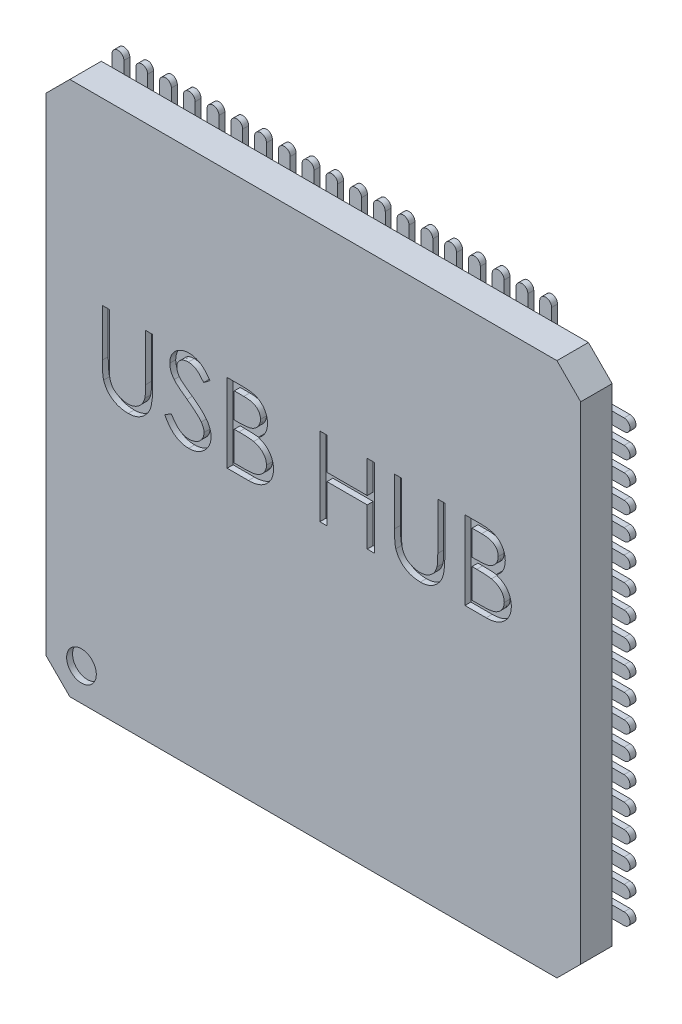
SolidWorks part; units mm, degrees
ref_plane "Front" through (0, 0, 0) normal (0, 0, 1) x (1, 0, 0)
ref_plane "Top" through (0, 0, 0) normal (0, 1, 0) x (1, 0, 0)
ref_plane "Right" through (0, 0, 0) normal (1, 0, 0) x (0, 0, -1)
ref_plane "Plan1" through (0, 0, 6.6297) normal (0, 0, -1) x (-1, 0, 0)
sketch "Esquisse1" plane through (0, 0, 6.6297) normal (0, 0, -1) x (-1, 0, 0)
  line L0 (-11.8985, 7.5604) -> (-11.8985, -1.4396)
  line L1 (-11.8985, -1.4396) -> (-2.8985, -1.4396)
  line L2 (-2.8985, -1.4396) -> (-2.8985, 7.5604)
  line L3 (-2.8985, 7.5604) -> (-11.8985, 7.5604)
extrude "Boss.-Extru.1" add sketch "Esquisse1" against normal blind 0.53
hole_wizard "Diamètre du perçage Ø0.5 (0.5)1" positions "Esquisse3" profile "Esquisse2" hole size "Ø0.5" standard "Ansi Metric"
sketch "Esquisse3" plane through (0, 0, 7.1597) normal (0, 0, 1) x (1, 0, 0)
  point P0 (3.4947, -0.8917)
sketch "Esquisse2" plane through (3.4947, -0.8917, 7.1597) normal (1, 0, 0) x (0, -1, 0)
  line L0 (0, 0) -> (0, 0.1)
  line L1 (0, 0.1) -> (0.25, 0.1)
  line L2 (0.25, 0.1) -> (0.25, 0)
  line L5 (0.25, 0) -> (0, 0)
  line L10 (0, 0.1) -> (-0.25, 0.1) construction
  line L11 (0, -6.35) -> (0, 107.95) construction
  dimension "Diamètre du perçage" = 0.5
  dimension "Profondeur du perçage" = 0.1
  dimension "Angle de pointe" = 180
chamfer "Chanfrein1" distance 0.4 angle 45 4 edges at (2.8985, 7.5604, 6.8947) (11.8985, 7.5604, 6.8947) (11.8985, -1.4396, 6.8947) (2.8985, -1.4396, 6.8947)
sketch "Esquisse4" plane through (0, 0, 6.6297) normal (0, 0, -1) x (-1, 0, 0)
  line L0 (-7.3985, 7.5604) -> (-7.3985, -1.4396) construction
  line L1 (-3.2985, 7.5604) -> (-11.4985, 7.5604) construction
  line L2 (-11.4985, -1.4396) -> (-3.2985, -1.4396) construction
  line L3 (-2.8985, 3.0604) -> (-11.8985, 3.0604) construction
  line L4 (-2.8985, -1.0396) -> (-2.8985, 7.1604) construction
  line L5 (-11.8985, 7.1604) -> (-11.8985, -1.0396) construction
  line L6 (-3.0985, 3.0604) -> (-2.6985, 3.0604) construction
  line L7 (-3.0985, 3.1604) -> (-2.6985, 3.1604)
  line L8 (-3.0985, 2.9604) -> (-2.6985, 2.9604)
  line L9 (-3.0985, 3.4604) -> (-2.6985, 3.4604) construction
  line L10 (-3.0985, 3.5604) -> (-2.6985, 3.5604)
  line L11 (-3.0985, 3.3604) -> (-2.6985, 3.3604)
  line L12 (-3.0985, 3.8604) -> (-2.6985, 3.8604) construction
  line L13 (-3.0985, 3.9604) -> (-2.6985, 3.9604)
  line L14 (-3.0985, 3.7604) -> (-2.6985, 3.7604)
  line L15 (-3.0985, 4.2604) -> (-2.6985, 4.2604) construction
  line L16 (-3.0985, 4.3604) -> (-2.6985, 4.3604)
  line L17 (-3.0985, 4.1604) -> (-2.6985, 4.1604)
  line L18 (-3.0985, 3.8604) -> (-2.6985, 3.8604) construction
  line L19 (-3.0985, 3.9604) -> (-2.6985, 3.9604)
  line L20 (-3.0985, 3.7604) -> (-2.6985, 3.7604)
  line L21 (-3.0985, 4.2604) -> (-2.6985, 4.2604) construction
  line L22 (-3.0985, 4.3604) -> (-2.6985, 4.3604)
  line L23 (-3.0985, 4.1604) -> (-2.6985, 4.1604)
  line L24 (-3.0985, 4.6604) -> (-2.6985, 4.6604) construction
  line L25 (-3.0985, 4.7604) -> (-2.6985, 4.7604)
  line L26 (-3.0985, 4.5604) -> (-2.6985, 4.5604)
  line L27 (-3.0985, 4.2604) -> (-2.6985, 4.2604) construction
  line L28 (-3.0985, 4.3604) -> (-2.6985, 4.3604)
  line L29 (-3.0985, 4.1604) -> (-2.6985, 4.1604)
  line L30 (-3.0985, 4.6604) -> (-2.6985, 4.6604) construction
  line L31 (-3.0985, 4.7604) -> (-2.6985, 4.7604)
  line L32 (-3.0985, 4.5604) -> (-2.6985, 4.5604)
  line L33 (-3.0985, 5.0604) -> (-2.6985, 5.0604) construction
  line L34 (-3.0985, 5.1604) -> (-2.6985, 5.1604)
  line L35 (-3.0985, 4.9604) -> (-2.6985, 4.9604)
  line L36 (-3.0985, 4.6604) -> (-2.6985, 4.6604) construction
  line L37 (-3.0985, 4.7604) -> (-2.6985, 4.7604)
  line L38 (-3.0985, 4.5604) -> (-2.6985, 4.5604)
  line L39 (-3.0985, 5.0604) -> (-2.6985, 5.0604) construction
  line L40 (-3.0985, 5.1604) -> (-2.6985, 5.1604)
  line L41 (-3.0985, 4.9604) -> (-2.6985, 4.9604)
  line L42 (-3.0985, 5.4604) -> (-2.6985, 5.4604) construction
  line L43 (-3.0985, 5.5604) -> (-2.6985, 5.5604)
  line L44 (-3.0985, 5.3604) -> (-2.6985, 5.3604)
  line L45 (-3.0985, 5.0604) -> (-2.6985, 5.0604) construction
  line L46 (-3.0985, 5.1604) -> (-2.6985, 5.1604)
  line L47 (-3.0985, 4.9604) -> (-2.6985, 4.9604)
  line L48 (-3.0985, 5.4604) -> (-2.6985, 5.4604) construction
  line L49 (-3.0985, 5.5604) -> (-2.6985, 5.5604)
  line L50 (-3.0985, 5.3604) -> (-2.6985, 5.3604)
  line L51 (-3.0985, 5.8604) -> (-2.6985, 5.8604) construction
  line L52 (-3.0985, 5.9604) -> (-2.6985, 5.9604)
  line L53 (-3.0985, 5.7604) -> (-2.6985, 5.7604)
  line L54 (-3.0985, 5.4604) -> (-2.6985, 5.4604) construction
  line L55 (-3.0985, 5.5604) -> (-2.6985, 5.5604)
  line L56 (-3.0985, 5.3604) -> (-2.6985, 5.3604)
  line L57 (-3.0985, 5.8604) -> (-2.6985, 5.8604) construction
  line L58 (-3.0985, 5.9604) -> (-2.6985, 5.9604)
  line L59 (-3.0985, 5.7604) -> (-2.6985, 5.7604)
  line L60 (-3.0985, 6.2604) -> (-2.6985, 6.2604) construction
  line L61 (-3.0985, 6.3604) -> (-2.6985, 6.3604)
  line L62 (-3.0985, 6.1604) -> (-2.6985, 6.1604)
  line L63 (-3.0985, 5.8604) -> (-2.6985, 5.8604) construction
  line L64 (-3.0985, 5.9604) -> (-2.6985, 5.9604)
  line L65 (-3.0985, 5.7604) -> (-2.6985, 5.7604)
  line L66 (-3.0985, 6.2604) -> (-2.6985, 6.2604) construction
  line L67 (-3.0985, 6.3604) -> (-2.6985, 6.3604)
  line L68 (-3.0985, 6.1604) -> (-2.6985, 6.1604)
  line L69 (-3.0985, 6.6604) -> (-2.6985, 6.6604) construction
  line L70 (-3.0985, 6.7604) -> (-2.6985, 6.7604)
  line L71 (-3.0985, 6.5604) -> (-2.6985, 6.5604)
  line L72 (-3.0985, 3.4604) -> (-2.6985, 3.4604) construction
  line L73 (-3.0985, 3.5604) -> (-2.6985, 3.5604)
  line L74 (-3.0985, 3.3604) -> (-2.6985, 3.3604)
  line L75 (-3.0985, 3.8604) -> (-2.6985, 3.8604) construction
  line L76 (-3.0985, 3.9604) -> (-2.6985, 3.9604)
  line L77 (-3.0985, 3.7604) -> (-2.6985, 3.7604)
  line L78 (-3.0985, 4.2604) -> (-2.6985, 4.2604) construction
  line L79 (-3.0985, 4.3604) -> (-2.6985, 4.3604)
  line L80 (-3.0985, 4.1604) -> (-2.6985, 4.1604)
  line L81 (-3.0985, 4.6604) -> (-2.6985, 4.6604) construction
  line L82 (-3.0985, 4.7604) -> (-2.6985, 4.7604)
  line L83 (-3.0985, 4.5604) -> (-2.6985, 4.5604)
  line L84 (-3.0985, 5.0604) -> (-2.6985, 5.0604) construction
  line L85 (-3.0985, 5.1604) -> (-2.6985, 5.1604)
  line L86 (-3.0985, 4.9604) -> (-2.6985, 4.9604)
  line L87 (-3.0985, 5.4604) -> (-2.6985, 5.4604) construction
  line L88 (-3.0985, 5.5604) -> (-2.6985, 5.5604)
  line L89 (-3.0985, 5.3604) -> (-2.6985, 5.3604)
  line L90 (-3.0985, 2.6604) -> (-2.6985, 2.6604) construction
  line L91 (-3.0985, 2.7604) -> (-2.6985, 2.7604)
  line L92 (-3.0985, 2.5604) -> (-2.6985, 2.5604)
  line L93 (-3.0985, 2.2604) -> (-2.6985, 2.2604) construction
  line L94 (-3.0985, 2.3604) -> (-2.6985, 2.3604)
  line L95 (-3.0985, 2.1604) -> (-2.6985, 2.1604)
  line L96 (-3.0985, 1.8604) -> (-2.6985, 1.8604) construction
  line L97 (-3.0985, 1.9604) -> (-2.6985, 1.9604)
  line L98 (-3.0985, 1.7604) -> (-2.6985, 1.7604)
  line L99 (-3.0985, 1.4604) -> (-2.6985, 1.4604) construction
  line L100 (-3.0985, 1.5604) -> (-2.6985, 1.5604)
  line L101 (-3.0985, 1.3604) -> (-2.6985, 1.3604)
  line L102 (-3.0985, 1.0604) -> (-2.6985, 1.0604) construction
  line L103 (-3.0985, 1.1604) -> (-2.6985, 1.1604)
  line L104 (-3.0985, 0.9604) -> (-2.6985, 0.9604)
  line L105 (-3.0985, 0.6604) -> (-2.6985, 0.6604) construction
  line L106 (-3.0985, 0.7604) -> (-2.6985, 0.7604)
  line L107 (-3.0985, 0.5604) -> (-2.6985, 0.5604)
  line L108 (-3.0985, 0.2604) -> (-2.6985, 0.2604) construction
  line L109 (-3.0985, 0.3604) -> (-2.6985, 0.3604)
  line L110 (-3.0985, 0.1604) -> (-2.6985, 0.1604)
  line L111 (-3.0985, -0.1396) -> (-2.6985, -0.1396) construction
  line L112 (-3.0985, -0.0396) -> (-2.6985, -0.0396)
  line L113 (-3.0985, -0.2396) -> (-2.6985, -0.2396)
  line L114 (-3.0985, -0.5396) -> (-2.6985, -0.5396) construction
  line L115 (-3.0985, -0.4396) -> (-2.6985, -0.4396)
  line L116 (-3.0985, -0.6396) -> (-2.6985, -0.6396)
  line L117 (-11.6985, -0.5396) -> (-12.0985, -0.5396) construction
  line L118 (-11.6985, -0.4396) -> (-12.0985, -0.4396)
  line L119 (-11.6985, -0.6396) -> (-12.0985, -0.6396)
  line L120 (-11.6985, -0.1396) -> (-12.0985, -0.1396) construction
  line L121 (-11.6985, -0.0396) -> (-12.0985, -0.0396)
  line L122 (-11.6985, -0.2396) -> (-12.0985, -0.2396)
  line L123 (-11.6985, 0.2604) -> (-12.0985, 0.2604) construction
  line L124 (-11.6985, 0.3604) -> (-12.0985, 0.3604)
  line L125 (-11.6985, 0.1604) -> (-12.0985, 0.1604)
  line L126 (-11.6985, 0.6604) -> (-12.0985, 0.6604) construction
  line L127 (-11.6985, 0.7604) -> (-12.0985, 0.7604)
  line L128 (-11.6985, 0.5604) -> (-12.0985, 0.5604)
  line L129 (-11.6985, 1.0604) -> (-12.0985, 1.0604) construction
  line L130 (-11.6985, 1.1604) -> (-12.0985, 1.1604)
  line L131 (-11.6985, 0.9604) -> (-12.0985, 0.9604)
  line L132 (-11.6985, 1.4604) -> (-12.0985, 1.4604) construction
  line L133 (-11.6985, 1.5604) -> (-12.0985, 1.5604)
  line L134 (-11.6985, 1.3604) -> (-12.0985, 1.3604)
  line L135 (-11.6985, 1.8604) -> (-12.0985, 1.8604) construction
  line L136 (-11.6985, 1.9604) -> (-12.0985, 1.9604)
  line L137 (-11.6985, 1.7604) -> (-12.0985, 1.7604)
  line L138 (-11.6985, 2.2604) -> (-12.0985, 2.2604) construction
  line L139 (-11.6985, 2.3604) -> (-12.0985, 2.3604)
  line L140 (-11.6985, 2.1604) -> (-12.0985, 2.1604)
  line L141 (-11.6985, 2.6604) -> (-12.0985, 2.6604) construction
  line L142 (-11.6985, 2.7604) -> (-12.0985, 2.7604)
  line L143 (-11.6985, 2.5604) -> (-12.0985, 2.5604)
  line L144 (-11.6985, 3.0604) -> (-12.0985, 3.0604) construction
  line L145 (-11.6985, 3.1604) -> (-12.0985, 3.1604)
  line L146 (-11.6985, 2.9604) -> (-12.0985, 2.9604)
  line L147 (-11.6985, 3.4604) -> (-12.0985, 3.4604) construction
  line L148 (-11.6985, 3.5604) -> (-12.0985, 3.5604)
  line L149 (-11.6985, 3.3604) -> (-12.0985, 3.3604)
  line L150 (-11.6985, 3.8604) -> (-12.0985, 3.8604) construction
  line L151 (-11.6985, 3.9604) -> (-12.0985, 3.9604)
  line L152 (-11.6985, 3.7604) -> (-12.0985, 3.7604)
  line L153 (-11.6985, 4.2604) -> (-12.0985, 4.2604) construction
  line L154 (-11.6985, 4.3604) -> (-12.0985, 4.3604)
  line L155 (-11.6985, 4.1604) -> (-12.0985, 4.1604)
  line L156 (-11.6985, 4.6604) -> (-12.0985, 4.6604) construction
  line L157 (-11.6985, 4.7604) -> (-12.0985, 4.7604)
  line L158 (-11.6985, 4.5604) -> (-12.0985, 4.5604)
  line L159 (-11.6985, 5.0604) -> (-12.0985, 5.0604) construction
  line L160 (-11.6985, 5.1604) -> (-12.0985, 5.1604)
  line L161 (-11.6985, 4.9604) -> (-12.0985, 4.9604)
  line L162 (-11.6985, 5.4604) -> (-12.0985, 5.4604) construction
  line L163 (-11.6985, 5.5604) -> (-12.0985, 5.5604)
  line L164 (-11.6985, 5.3604) -> (-12.0985, 5.3604)
  line L165 (-11.6985, 5.8604) -> (-12.0985, 5.8604) construction
  line L166 (-11.6985, 5.9604) -> (-12.0985, 5.9604)
  line L167 (-11.6985, 5.7604) -> (-12.0985, 5.7604)
  line L168 (-11.6985, 6.2604) -> (-12.0985, 6.2604) construction
  line L169 (-11.6985, 6.3604) -> (-12.0985, 6.3604)
  line L170 (-11.6985, 6.1604) -> (-12.0985, 6.1604)
  line L171 (-11.6985, 6.6604) -> (-12.0985, 6.6604) construction
  line L172 (-11.6985, 6.7604) -> (-12.0985, 6.7604)
  line L173 (-11.6985, 6.5604) -> (-12.0985, 6.5604)
  line L174 (-2.8985, 3.0604) -> (-11.8985, 3.0604) construction
  line L175 (-3.9785, 7.3604) -> (-3.9785, 7.7604) construction
  line L178 (-3.8785, 7.3604) -> (-3.8785, 7.7604)
  line L181 (-4.0785, 7.3604) -> (-4.0785, 7.7604)
  line L184 (-4.3785, 7.3604) -> (-4.3785, 7.7604) construction
  line L187 (-4.2785, 7.3604) -> (-4.2785, 7.7604)
  line L190 (-4.4785, 7.3604) -> (-4.4785, 7.7604)
  line L193 (-4.7785, 7.3604) -> (-4.7785, 7.7604) construction
  line L196 (-4.6785, 7.3604) -> (-4.6785, 7.7604)
  line L199 (-4.8785, 7.3604) -> (-4.8785, 7.7604)
  line L202 (-5.1785, 7.3604) -> (-5.1785, 7.7604) construction
  line L205 (-5.0785, 7.3604) -> (-5.0785, 7.7604)
  line L208 (-5.2785, 7.3604) -> (-5.2785, 7.7604)
  line L211 (-5.5785, 7.3604) -> (-5.5785, 7.7604) construction
  line L214 (-5.4785, 7.3604) -> (-5.4785, 7.7604)
  line L217 (-5.6785, 7.3604) -> (-5.6785, 7.7604)
  line L220 (-5.9785, 7.3604) -> (-5.9785, 7.7604) construction
  line L223 (-5.8785, 7.3604) -> (-5.8785, 7.7604)
  line L226 (-6.0785, 7.3604) -> (-6.0785, 7.7604)
  line L229 (-6.3785, 7.3604) -> (-6.3785, 7.7604) construction
  line L232 (-6.2785, 7.3604) -> (-6.2785, 7.7604)
  line L235 (-6.4785, 7.3604) -> (-6.4785, 7.7604)
  line L238 (-6.7785, 7.3604) -> (-6.7785, 7.7604) construction
  line L241 (-6.6785, 7.3604) -> (-6.6785, 7.7604)
  line L244 (-6.8785, 7.3604) -> (-6.8785, 7.7604)
  line L247 (-7.1785, 7.3604) -> (-7.1785, 7.7604) construction
  line L250 (-7.0785, 7.3604) -> (-7.0785, 7.7604)
  line L253 (-7.2785, 7.3604) -> (-7.2785, 7.7604)
  line L256 (-7.5785, 7.3604) -> (-7.5785, 7.7604) construction
  line L259 (-7.4785, 7.3604) -> (-7.4785, 7.7604)
  line L262 (-7.6785, 7.3604) -> (-7.6785, 7.7604)
  line L265 (-7.9785, 7.3604) -> (-7.9785, 7.7604) construction
  line L268 (-7.8785, 7.3604) -> (-7.8785, 7.7604)
  line L271 (-8.0785, 7.3604) -> (-8.0785, 7.7604)
  line L274 (-8.3785, 7.3604) -> (-8.3785, 7.7604) construction
  line L277 (-8.2785, 7.3604) -> (-8.2785, 7.7604)
  line L280 (-8.4785, 7.3604) -> (-8.4785, 7.7604)
  line L283 (-8.7785, 7.3604) -> (-8.7785, 7.7604) construction
  line L286 (-3.5785, 7.3604) -> (-3.5785, 7.7604) construction
  line L287 (-3.4785, 7.3604) -> (-3.4785, 7.7604)
  line L288 (-3.6785, 7.3604) -> (-3.6785, 7.7604)
  line L289 (-8.6785, 7.3604) -> (-8.6785, 7.7604)
  line L290 (-10.4485, 0.0104) -> (-4.3485, 0.0104)
  line L291 (-10.4485, 0.0104) -> (-10.4485, 6.1104)
  line L292 (-10.4485, 6.1104) -> (-4.3485, 6.1104)
  line L293 (-4.3485, 0.0104) -> (-4.3485, 6.1104)
  line L294 (-10.4485, 0.0104) -> (-4.3485, 6.1104) construction
  line L295 (-10.4485, 6.1104) -> (-4.3485, 0.0104) construction
  line L296 (-8.8785, 7.3604) -> (-8.8785, 7.7604)
  line L297 (-9.1785, 7.3604) -> (-9.1785, 7.7604) construction
  line L298 (-9.0785, 7.3604) -> (-9.0785, 7.7604)
  line L299 (-9.2785, 7.3604) -> (-9.2785, 7.7604)
  line L300 (-9.5785, 7.3604) -> (-9.5785, 7.7604) construction
  line L301 (-9.4785, 7.3604) -> (-9.4785, 7.7604)
  line L302 (-9.6785, 7.3604) -> (-9.6785, 7.7604)
  line L303 (-9.9785, 7.3604) -> (-9.9785, 7.7604) construction
  line L304 (-9.8785, 7.3604) -> (-9.8785, 7.7604)
  line L305 (-10.0785, 7.3604) -> (-10.0785, 7.7604)
  line L306 (-10.3785, 7.3604) -> (-10.3785, 7.7604) construction
  line L307 (-10.2785, 7.3604) -> (-10.2785, 7.7604)
  line L308 (-10.4785, 7.3604) -> (-10.4785, 7.7604)
  line L309 (-10.7785, 7.3604) -> (-10.7785, 7.7604) construction
  line L310 (-10.6785, 7.3604) -> (-10.6785, 7.7604)
  line L311 (-10.8785, 7.3604) -> (-10.8785, 7.7604)
  line L312 (-3.5785, -1.2396) -> (-3.5785, -1.6396) construction
  line L313 (-3.4785, -1.2396) -> (-3.4785, -1.6396)
  line L314 (-3.6785, -1.2396) -> (-3.6785, -1.6396)
  line L315 (-10.7785, -1.2396) -> (-10.7785, -1.6396) construction
  line L316 (-10.6785, -1.2396) -> (-10.6785, -1.6396)
  line L317 (-10.8785, -1.2396) -> (-10.8785, -1.6396)
  line L318 (-10.3785, -1.2396) -> (-10.3785, -1.6396) construction
  line L319 (-10.2785, -1.2396) -> (-10.2785, -1.6396)
  line L320 (-10.4785, -1.2396) -> (-10.4785, -1.6396)
  line L321 (-9.9785, -1.2396) -> (-9.9785, -1.6396) construction
  line L322 (-9.8785, -1.2396) -> (-9.8785, -1.6396)
  line L323 (-10.0785, -1.2396) -> (-10.0785, -1.6396)
  line L324 (-9.5785, -1.2396) -> (-9.5785, -1.6396) construction
  line L325 (-9.4785, -1.2396) -> (-9.4785, -1.6396)
  line L326 (-9.6785, -1.2396) -> (-9.6785, -1.6396)
  line L327 (-9.1785, -1.2396) -> (-9.1785, -1.6396) construction
  line L328 (-9.0785, -1.2396) -> (-9.0785, -1.6396)
  line L329 (-9.2785, -1.2396) -> (-9.2785, -1.6396)
  line L330 (-8.7785, -1.2396) -> (-8.7785, -1.6396) construction
  line L331 (-8.6785, -1.2396) -> (-8.6785, -1.6396)
  line L332 (-8.8785, -1.2396) -> (-8.8785, -1.6396)
  line L333 (-8.3785, -1.2396) -> (-8.3785, -1.6396) construction
  line L334 (-8.2785, -1.2396) -> (-8.2785, -1.6396)
  line L335 (-8.4785, -1.2396) -> (-8.4785, -1.6396)
  line L336 (-7.9785, -1.2396) -> (-7.9785, -1.6396) construction
  line L337 (-7.8785, -1.2396) -> (-7.8785, -1.6396)
  line L338 (-8.0785, -1.2396) -> (-8.0785, -1.6396)
  line L339 (-7.5785, -1.2396) -> (-7.5785, -1.6396) construction
  line L340 (-7.4785, -1.2396) -> (-7.4785, -1.6396)
  line L341 (-7.6785, -1.2396) -> (-7.6785, -1.6396)
  line L342 (-7.1785, -1.2396) -> (-7.1785, -1.6396) construction
  line L343 (-7.0785, -1.2396) -> (-7.0785, -1.6396)
  line L344 (-7.2785, -1.2396) -> (-7.2785, -1.6396)
  line L345 (-6.7785, -1.2396) -> (-6.7785, -1.6396) construction
  line L346 (-6.6785, -1.2396) -> (-6.6785, -1.6396)
  line L347 (-6.8785, -1.2396) -> (-6.8785, -1.6396)
  line L348 (-6.3785, -1.2396) -> (-6.3785, -1.6396) construction
  line L349 (-6.2785, -1.2396) -> (-6.2785, -1.6396)
  line L350 (-6.4785, -1.2396) -> (-6.4785, -1.6396)
  line L351 (-5.9785, -1.2396) -> (-5.9785, -1.6396) construction
  line L352 (-5.8785, -1.2396) -> (-5.8785, -1.6396)
  line L353 (-6.0785, -1.2396) -> (-6.0785, -1.6396)
  line L354 (-5.5785, -1.2396) -> (-5.5785, -1.6396) construction
  line L355 (-5.4785, -1.2396) -> (-5.4785, -1.6396)
  line L356 (-5.6785, -1.2396) -> (-5.6785, -1.6396)
  line L357 (-5.1785, -1.2396) -> (-5.1785, -1.6396) construction
  line L358 (-5.0785, -1.2396) -> (-5.0785, -1.6396)
  line L359 (-5.2785, -1.2396) -> (-5.2785, -1.6396)
  line L360 (-4.7785, -1.2396) -> (-4.7785, -1.6396) construction
  line L361 (-4.6785, -1.2396) -> (-4.6785, -1.6396)
  line L362 (-4.8785, -1.2396) -> (-4.8785, -1.6396)
  line L363 (-4.3785, -1.2396) -> (-4.3785, -1.6396) construction
  line L364 (-4.2785, -1.2396) -> (-4.2785, -1.6396)
  line L365 (-4.4785, -1.2396) -> (-4.4785, -1.6396)
  line L366 (-3.9785, -1.2396) -> (-3.9785, -1.6396) construction
  line L367 (-3.8785, -1.2396) -> (-3.8785, -1.6396)
  line L368 (-4.0785, -1.2396) -> (-4.0785, -1.6396)
  arc A0 (-3.0985, 3.1604) -> (-3.0985, 2.9604) centre (-3.0985, 3.0604) ccw
  arc A1 (-2.6985, 2.9604) -> (-2.6985, 3.1604) centre (-2.6985, 3.0604) ccw
  arc A2 (-3.0985, 3.5604) -> (-3.0985, 3.3604) centre (-3.0985, 3.4604) ccw
  arc A3 (-2.6985, 3.3604) -> (-2.6985, 3.5604) centre (-2.6985, 3.4604) ccw
  arc A4 (-3.0985, 3.9604) -> (-3.0985, 3.7604) centre (-3.0985, 3.8604) ccw
  arc A5 (-2.6985, 3.7604) -> (-2.6985, 3.9604) centre (-2.6985, 3.8604) ccw
  arc A6 (-3.0985, 4.3604) -> (-3.0985, 4.1604) centre (-3.0985, 4.2604) ccw
  arc A7 (-2.6985, 4.1604) -> (-2.6985, 4.3604) centre (-2.6985, 4.2604) ccw
  arc A8 (-3.0985, 3.9604) -> (-3.0985, 3.7604) centre (-3.0985, 3.8604) ccw
  arc A9 (-2.6985, 3.7604) -> (-2.6985, 3.9604) centre (-2.6985, 3.8604) ccw
  arc A10 (-3.0985, 4.3604) -> (-3.0985, 4.1604) centre (-3.0985, 4.2604) ccw
  arc A11 (-2.6985, 4.1604) -> (-2.6985, 4.3604) centre (-2.6985, 4.2604) ccw
  arc A12 (-3.0985, 4.7604) -> (-3.0985, 4.5604) centre (-3.0985, 4.6604) ccw
  arc A13 (-2.6985, 4.5604) -> (-2.6985, 4.7604) centre (-2.6985, 4.6604) ccw
  arc A14 (-3.0985, 4.3604) -> (-3.0985, 4.1604) centre (-3.0985, 4.2604) ccw
  arc A15 (-2.6985, 4.1604) -> (-2.6985, 4.3604) centre (-2.6985, 4.2604) ccw
  arc A16 (-3.0985, 4.7604) -> (-3.0985, 4.5604) centre (-3.0985, 4.6604) ccw
  arc A17 (-2.6985, 4.5604) -> (-2.6985, 4.7604) centre (-2.6985, 4.6604) ccw
  arc A18 (-3.0985, 5.1604) -> (-3.0985, 4.9604) centre (-3.0985, 5.0604) ccw
  arc A19 (-2.6985, 4.9604) -> (-2.6985, 5.1604) centre (-2.6985, 5.0604) ccw
  arc A20 (-3.0985, 4.7604) -> (-3.0985, 4.5604) centre (-3.0985, 4.6604) ccw
  arc A21 (-2.6985, 4.5604) -> (-2.6985, 4.7604) centre (-2.6985, 4.6604) ccw
  arc A22 (-3.0985, 5.1604) -> (-3.0985, 4.9604) centre (-3.0985, 5.0604) ccw
  arc A23 (-2.6985, 4.9604) -> (-2.6985, 5.1604) centre (-2.6985, 5.0604) ccw
  arc A24 (-3.0985, 5.5604) -> (-3.0985, 5.3604) centre (-3.0985, 5.4604) ccw
  arc A25 (-2.6985, 5.3604) -> (-2.6985, 5.5604) centre (-2.6985, 5.4604) ccw
  arc A26 (-3.0985, 5.1604) -> (-3.0985, 4.9604) centre (-3.0985, 5.0604) ccw
  arc A27 (-2.6985, 4.9604) -> (-2.6985, 5.1604) centre (-2.6985, 5.0604) ccw
  arc A28 (-3.0985, 5.5604) -> (-3.0985, 5.3604) centre (-3.0985, 5.4604) ccw
  arc A29 (-2.6985, 5.3604) -> (-2.6985, 5.5604) centre (-2.6985, 5.4604) ccw
  arc A30 (-3.0985, 5.9604) -> (-3.0985, 5.7604) centre (-3.0985, 5.8604) ccw
  arc A31 (-2.6985, 5.7604) -> (-2.6985, 5.9604) centre (-2.6985, 5.8604) ccw
  arc A32 (-3.0985, 5.5604) -> (-3.0985, 5.3604) centre (-3.0985, 5.4604) ccw
  arc A33 (-2.6985, 5.3604) -> (-2.6985, 5.5604) centre (-2.6985, 5.4604) ccw
  arc A34 (-3.0985, 5.9604) -> (-3.0985, 5.7604) centre (-3.0985, 5.8604) ccw
  arc A35 (-2.6985, 5.7604) -> (-2.6985, 5.9604) centre (-2.6985, 5.8604) ccw
  arc A36 (-3.0985, 6.3604) -> (-3.0985, 6.1604) centre (-3.0985, 6.2604) ccw
  arc A37 (-2.6985, 6.1604) -> (-2.6985, 6.3604) centre (-2.6985, 6.2604) ccw
  arc A38 (-3.0985, 5.9604) -> (-3.0985, 5.7604) centre (-3.0985, 5.8604) ccw
  arc A39 (-2.6985, 5.7604) -> (-2.6985, 5.9604) centre (-2.6985, 5.8604) ccw
  arc A40 (-3.0985, 6.3604) -> (-3.0985, 6.1604) centre (-3.0985, 6.2604) ccw
  arc A41 (-2.6985, 6.1604) -> (-2.6985, 6.3604) centre (-2.6985, 6.2604) ccw
  arc A42 (-3.0985, 6.7604) -> (-3.0985, 6.5604) centre (-3.0985, 6.6604) ccw
  arc A43 (-2.6985, 6.5604) -> (-2.6985, 6.7604) centre (-2.6985, 6.6604) ccw
  arc A44 (-3.0985, 3.5604) -> (-3.0985, 3.3604) centre (-3.0985, 3.4604) ccw
  arc A45 (-2.6985, 3.3604) -> (-2.6985, 3.5604) centre (-2.6985, 3.4604) ccw
  arc A46 (-3.0985, 3.9604) -> (-3.0985, 3.7604) centre (-3.0985, 3.8604) ccw
  arc A47 (-2.6985, 3.7604) -> (-2.6985, 3.9604) centre (-2.6985, 3.8604) ccw
  arc A48 (-3.0985, 4.3604) -> (-3.0985, 4.1604) centre (-3.0985, 4.2604) ccw
  arc A49 (-2.6985, 4.1604) -> (-2.6985, 4.3604) centre (-2.6985, 4.2604) ccw
  arc A50 (-3.0985, 4.7604) -> (-3.0985, 4.5604) centre (-3.0985, 4.6604) ccw
  arc A51 (-2.6985, 4.5604) -> (-2.6985, 4.7604) centre (-2.6985, 4.6604) ccw
  arc A52 (-3.0985, 5.1604) -> (-3.0985, 4.9604) centre (-3.0985, 5.0604) ccw
  arc A53 (-2.6985, 4.9604) -> (-2.6985, 5.1604) centre (-2.6985, 5.0604) ccw
  arc A54 (-3.0985, 5.5604) -> (-3.0985, 5.3604) centre (-3.0985, 5.4604) ccw
  arc A55 (-2.6985, 5.3604) -> (-2.6985, 5.5604) centre (-2.6985, 5.4604) ccw
  arc A56 (-3.0985, 2.7604) -> (-3.0985, 2.5604) centre (-3.0985, 2.6604) ccw
  arc A57 (-2.6985, 2.5604) -> (-2.6985, 2.7604) centre (-2.6985, 2.6604) ccw
  arc A58 (-3.0985, 2.3604) -> (-3.0985, 2.1604) centre (-3.0985, 2.2604) ccw
  arc A59 (-2.6985, 2.1604) -> (-2.6985, 2.3604) centre (-2.6985, 2.2604) ccw
  arc A60 (-3.0985, 1.9604) -> (-3.0985, 1.7604) centre (-3.0985, 1.8604) ccw
  arc A61 (-2.6985, 1.7604) -> (-2.6985, 1.9604) centre (-2.6985, 1.8604) ccw
  arc A62 (-3.0985, 1.5604) -> (-3.0985, 1.3604) centre (-3.0985, 1.4604) ccw
  arc A63 (-2.6985, 1.3604) -> (-2.6985, 1.5604) centre (-2.6985, 1.4604) ccw
  arc A64 (-3.0985, 1.1604) -> (-3.0985, 0.9604) centre (-3.0985, 1.0604) ccw
  arc A65 (-2.6985, 0.9604) -> (-2.6985, 1.1604) centre (-2.6985, 1.0604) ccw
  arc A66 (-3.0985, 0.7604) -> (-3.0985, 0.5604) centre (-3.0985, 0.6604) ccw
  arc A67 (-2.6985, 0.5604) -> (-2.6985, 0.7604) centre (-2.6985, 0.6604) ccw
  arc A68 (-3.0985, 0.3604) -> (-3.0985, 0.1604) centre (-3.0985, 0.2604) ccw
  arc A69 (-2.6985, 0.1604) -> (-2.6985, 0.3604) centre (-2.6985, 0.2604) ccw
  arc A70 (-3.0985, -0.0396) -> (-3.0985, -0.2396) centre (-3.0985, -0.1396) ccw
  arc A71 (-2.6985, -0.2396) -> (-2.6985, -0.0396) centre (-2.6985, -0.1396) ccw
  arc A72 (-3.0985, -0.4396) -> (-3.0985, -0.6396) centre (-3.0985, -0.5396) ccw
  arc A73 (-2.6985, -0.6396) -> (-2.6985, -0.4396) centre (-2.6985, -0.5396) ccw
  arc A74 (-11.6985, -0.4396) -> (-11.6985, -0.6396) centre (-11.6985, -0.5396) cw
  arc A75 (-12.0985, -0.6396) -> (-12.0985, -0.4396) centre (-12.0985, -0.5396) cw
  arc A76 (-11.6985, -0.0396) -> (-11.6985, -0.2396) centre (-11.6985, -0.1396) cw
  arc A77 (-12.0985, -0.2396) -> (-12.0985, -0.0396) centre (-12.0985, -0.1396) cw
  arc A78 (-11.6985, 0.3604) -> (-11.6985, 0.1604) centre (-11.6985, 0.2604) cw
  arc A79 (-12.0985, 0.1604) -> (-12.0985, 0.3604) centre (-12.0985, 0.2604) cw
  arc A80 (-11.6985, 0.7604) -> (-11.6985, 0.5604) centre (-11.6985, 0.6604) cw
  arc A81 (-12.0985, 0.5604) -> (-12.0985, 0.7604) centre (-12.0985, 0.6604) cw
  arc A82 (-11.6985, 1.1604) -> (-11.6985, 0.9604) centre (-11.6985, 1.0604) cw
  arc A83 (-12.0985, 0.9604) -> (-12.0985, 1.1604) centre (-12.0985, 1.0604) cw
  arc A84 (-11.6985, 1.5604) -> (-11.6985, 1.3604) centre (-11.6985, 1.4604) cw
  arc A85 (-12.0985, 1.3604) -> (-12.0985, 1.5604) centre (-12.0985, 1.4604) cw
  arc A86 (-11.6985, 1.9604) -> (-11.6985, 1.7604) centre (-11.6985, 1.8604) cw
  arc A87 (-12.0985, 1.7604) -> (-12.0985, 1.9604) centre (-12.0985, 1.8604) cw
  arc A88 (-11.6985, 2.3604) -> (-11.6985, 2.1604) centre (-11.6985, 2.2604) cw
  arc A89 (-12.0985, 2.1604) -> (-12.0985, 2.3604) centre (-12.0985, 2.2604) cw
  arc A90 (-11.6985, 2.7604) -> (-11.6985, 2.5604) centre (-11.6985, 2.6604) cw
  arc A91 (-12.0985, 2.5604) -> (-12.0985, 2.7604) centre (-12.0985, 2.6604) cw
  arc A92 (-11.6985, 3.1604) -> (-11.6985, 2.9604) centre (-11.6985, 3.0604) cw
  arc A93 (-12.0985, 2.9604) -> (-12.0985, 3.1604) centre (-12.0985, 3.0604) cw
  arc A94 (-11.6985, 3.5604) -> (-11.6985, 3.3604) centre (-11.6985, 3.4604) cw
  arc A95 (-12.0985, 3.3604) -> (-12.0985, 3.5604) centre (-12.0985, 3.4604) cw
  arc A96 (-11.6985, 3.9604) -> (-11.6985, 3.7604) centre (-11.6985, 3.8604) cw
  arc A97 (-12.0985, 3.7604) -> (-12.0985, 3.9604) centre (-12.0985, 3.8604) cw
  arc A98 (-11.6985, 4.3604) -> (-11.6985, 4.1604) centre (-11.6985, 4.2604) cw
  arc A99 (-12.0985, 4.1604) -> (-12.0985, 4.3604) centre (-12.0985, 4.2604) cw
  arc A100 (-11.6985, 4.7604) -> (-11.6985, 4.5604) centre (-11.6985, 4.6604) cw
  arc A101 (-12.0985, 4.5604) -> (-12.0985, 4.7604) centre (-12.0985, 4.6604) cw
  arc A102 (-11.6985, 5.1604) -> (-11.6985, 4.9604) centre (-11.6985, 5.0604) cw
  arc A103 (-12.0985, 4.9604) -> (-12.0985, 5.1604) centre (-12.0985, 5.0604) cw
  arc A104 (-11.6985, 5.5604) -> (-11.6985, 5.3604) centre (-11.6985, 5.4604) cw
  arc A105 (-12.0985, 5.3604) -> (-12.0985, 5.5604) centre (-12.0985, 5.4604) cw
  arc A106 (-11.6985, 5.9604) -> (-11.6985, 5.7604) centre (-11.6985, 5.8604) cw
  arc A107 (-12.0985, 5.7604) -> (-12.0985, 5.9604) centre (-12.0985, 5.8604) cw
  arc A108 (-11.6985, 6.3604) -> (-11.6985, 6.1604) centre (-11.6985, 6.2604) cw
  arc A109 (-12.0985, 6.1604) -> (-12.0985, 6.3604) centre (-12.0985, 6.2604) cw
  arc A110 (-11.6985, 6.7604) -> (-11.6985, 6.5604) centre (-11.6985, 6.6604) cw
  arc A111 (-12.0985, 6.5604) -> (-12.0985, 6.7604) centre (-12.0985, 6.6604) cw
  arc A186 (-3.4785, 7.3604) -> (-3.6785, 7.3604) centre (-3.5785, 7.3604) cw
  arc A187 (-3.6785, 7.7604) -> (-3.4785, 7.7604) centre (-3.5785, 7.7604) cw
  arc A188 (-3.8785, 7.3604) -> (-4.0785, 7.3604) centre (-3.9785, 7.3604) cw
  arc A189 (-4.0785, 7.7604) -> (-3.8785, 7.7604) centre (-3.9785, 7.7604) cw
  arc A190 (-4.2785, 7.3604) -> (-4.4785, 7.3604) centre (-4.3785, 7.3604) cw
  arc A191 (-4.4785, 7.7604) -> (-4.2785, 7.7604) centre (-4.3785, 7.7604) cw
  arc A192 (-4.6785, 7.3604) -> (-4.8785, 7.3604) centre (-4.7785, 7.3604) cw
  arc A193 (-4.8785, 7.7604) -> (-4.6785, 7.7604) centre (-4.7785, 7.7604) cw
  arc A194 (-5.0785, 7.3604) -> (-5.2785, 7.3604) centre (-5.1785, 7.3604) cw
  arc A195 (-5.2785, 7.7604) -> (-5.0785, 7.7604) centre (-5.1785, 7.7604) cw
  arc A196 (-5.4785, 7.3604) -> (-5.6785, 7.3604) centre (-5.5785, 7.3604) cw
  arc A197 (-5.6785, 7.7604) -> (-5.4785, 7.7604) centre (-5.5785, 7.7604) cw
  arc A198 (-5.8785, 7.3604) -> (-6.0785, 7.3604) centre (-5.9785, 7.3604) cw
  arc A199 (-6.0785, 7.7604) -> (-5.8785, 7.7604) centre (-5.9785, 7.7604) cw
  arc A200 (-6.2785, 7.3604) -> (-6.4785, 7.3604) centre (-6.3785, 7.3604) cw
  arc A201 (-6.4785, 7.7604) -> (-6.2785, 7.7604) centre (-6.3785, 7.7604) cw
  arc A202 (-6.6785, 7.3604) -> (-6.8785, 7.3604) centre (-6.7785, 7.3604) cw
  arc A203 (-6.8785, 7.7604) -> (-6.6785, 7.7604) centre (-6.7785, 7.7604) cw
  arc A204 (-7.0785, 7.3604) -> (-7.2785, 7.3604) centre (-7.1785, 7.3604) cw
  arc A205 (-7.2785, 7.7604) -> (-7.0785, 7.7604) centre (-7.1785, 7.7604) cw
  arc A206 (-7.4785, 7.3604) -> (-7.6785, 7.3604) centre (-7.5785, 7.3604) cw
  arc A207 (-7.6785, 7.7604) -> (-7.4785, 7.7604) centre (-7.5785, 7.7604) cw
  arc A208 (-7.8785, 7.3604) -> (-8.0785, 7.3604) centre (-7.9785, 7.3604) cw
  arc A209 (-8.0785, 7.7604) -> (-7.8785, 7.7604) centre (-7.9785, 7.7604) cw
  arc A210 (-8.2785, 7.3604) -> (-8.4785, 7.3604) centre (-8.3785, 7.3604) cw
  arc A211 (-8.4785, 7.7604) -> (-8.2785, 7.7604) centre (-8.3785, 7.7604) cw
  arc A212 (-8.6785, 7.3604) -> (-8.8785, 7.3604) centre (-8.7785, 7.3604) cw
  arc A213 (-8.8785, 7.7604) -> (-8.6785, 7.7604) centre (-8.7785, 7.7604) cw
  arc A214 (-9.0785, 7.3604) -> (-9.2785, 7.3604) centre (-9.1785, 7.3604) cw
  arc A215 (-9.2785, 7.7604) -> (-9.0785, 7.7604) centre (-9.1785, 7.7604) cw
  arc A216 (-9.4785, 7.3604) -> (-9.6785, 7.3604) centre (-9.5785, 7.3604) cw
  arc A217 (-9.6785, 7.7604) -> (-9.4785, 7.7604) centre (-9.5785, 7.7604) cw
  arc A218 (-9.8785, 7.3604) -> (-10.0785, 7.3604) centre (-9.9785, 7.3604) cw
  arc A219 (-10.0785, 7.7604) -> (-9.8785, 7.7604) centre (-9.9785, 7.7604) cw
  arc A220 (-10.2785, 7.3604) -> (-10.4785, 7.3604) centre (-10.3785, 7.3604) cw
  arc A221 (-10.4785, 7.7604) -> (-10.2785, 7.7604) centre (-10.3785, 7.7604) cw
  arc A222 (-10.6785, 7.3604) -> (-10.8785, 7.3604) centre (-10.7785, 7.3604) cw
  arc A223 (-10.8785, 7.7604) -> (-10.6785, 7.7604) centre (-10.7785, 7.7604) cw
  arc A224 (-3.4785, -1.2396) -> (-3.6785, -1.2396) centre (-3.5785, -1.2396) ccw
  arc A225 (-3.6785, -1.6396) -> (-3.4785, -1.6396) centre (-3.5785, -1.6396) ccw
  arc A226 (-10.6785, -1.2396) -> (-10.8785, -1.2396) centre (-10.7785, -1.2396) ccw
  arc A227 (-10.8785, -1.6396) -> (-10.6785, -1.6396) centre (-10.7785, -1.6396) ccw
  arc A228 (-10.2785, -1.2396) -> (-10.4785, -1.2396) centre (-10.3785, -1.2396) ccw
  arc A229 (-10.4785, -1.6396) -> (-10.2785, -1.6396) centre (-10.3785, -1.6396) ccw
  arc A230 (-9.8785, -1.2396) -> (-10.0785, -1.2396) centre (-9.9785, -1.2396) ccw
  arc A231 (-10.0785, -1.6396) -> (-9.8785, -1.6396) centre (-9.9785, -1.6396) ccw
  arc A232 (-9.4785, -1.2396) -> (-9.6785, -1.2396) centre (-9.5785, -1.2396) ccw
  arc A233 (-9.6785, -1.6396) -> (-9.4785, -1.6396) centre (-9.5785, -1.6396) ccw
  arc A234 (-9.0785, -1.2396) -> (-9.2785, -1.2396) centre (-9.1785, -1.2396) ccw
  arc A235 (-9.2785, -1.6396) -> (-9.0785, -1.6396) centre (-9.1785, -1.6396) ccw
  arc A236 (-8.6785, -1.2396) -> (-8.8785, -1.2396) centre (-8.7785, -1.2396) ccw
  arc A237 (-8.8785, -1.6396) -> (-8.6785, -1.6396) centre (-8.7785, -1.6396) ccw
  arc A238 (-8.2785, -1.2396) -> (-8.4785, -1.2396) centre (-8.3785, -1.2396) ccw
  arc A239 (-8.4785, -1.6396) -> (-8.2785, -1.6396) centre (-8.3785, -1.6396) ccw
  arc A240 (-7.8785, -1.2396) -> (-8.0785, -1.2396) centre (-7.9785, -1.2396) ccw
  arc A241 (-8.0785, -1.6396) -> (-7.8785, -1.6396) centre (-7.9785, -1.6396) ccw
  arc A242 (-7.4785, -1.2396) -> (-7.6785, -1.2396) centre (-7.5785, -1.2396) ccw
  arc A243 (-7.6785, -1.6396) -> (-7.4785, -1.6396) centre (-7.5785, -1.6396) ccw
  arc A244 (-7.0785, -1.2396) -> (-7.2785, -1.2396) centre (-7.1785, -1.2396) ccw
  arc A245 (-7.2785, -1.6396) -> (-7.0785, -1.6396) centre (-7.1785, -1.6396) ccw
  arc A246 (-6.6785, -1.2396) -> (-6.8785, -1.2396) centre (-6.7785, -1.2396) ccw
  arc A247 (-6.8785, -1.6396) -> (-6.6785, -1.6396) centre (-6.7785, -1.6396) ccw
  arc A248 (-6.2785, -1.2396) -> (-6.4785, -1.2396) centre (-6.3785, -1.2396) ccw
  arc A249 (-6.4785, -1.6396) -> (-6.2785, -1.6396) centre (-6.3785, -1.6396) ccw
  arc A250 (-5.8785, -1.2396) -> (-6.0785, -1.2396) centre (-5.9785, -1.2396) ccw
  arc A251 (-6.0785, -1.6396) -> (-5.8785, -1.6396) centre (-5.9785, -1.6396) ccw
  arc A252 (-5.4785, -1.2396) -> (-5.6785, -1.2396) centre (-5.5785, -1.2396) ccw
  arc A253 (-5.6785, -1.6396) -> (-5.4785, -1.6396) centre (-5.5785, -1.6396) ccw
  arc A254 (-5.0785, -1.2396) -> (-5.2785, -1.2396) centre (-5.1785, -1.2396) ccw
  arc A255 (-5.2785, -1.6396) -> (-5.0785, -1.6396) centre (-5.1785, -1.6396) ccw
  arc A256 (-4.6785, -1.2396) -> (-4.8785, -1.2396) centre (-4.7785, -1.2396) ccw
  arc A257 (-4.8785, -1.6396) -> (-4.6785, -1.6396) centre (-4.7785, -1.6396) ccw
  arc A258 (-4.2785, -1.2396) -> (-4.4785, -1.2396) centre (-4.3785, -1.2396) ccw
  arc A259 (-4.4785, -1.6396) -> (-4.2785, -1.6396) centre (-4.3785, -1.6396) ccw
  arc A260 (-3.8785, -1.2396) -> (-4.0785, -1.2396) centre (-3.9785, -1.2396) ccw
  arc A261 (-4.0785, -1.6396) -> (-3.8785, -1.6396) centre (-3.9785, -1.6396) ccw
  point P14 (-2.8985, 3.0604)
  point P23 (-2.8985, 3.4604)
  point P30 (-2.8985, 3.8604)
  point P37 (-2.8985, 4.2604)
  point P44 (-2.8985, 3.8604)
  point P51 (-2.8985, 4.2604)
  point P58 (-2.8985, 4.6604)
  point P65 (-2.8985, 4.2604)
  point P72 (-2.8985, 4.6604)
  point P79 (-2.8985, 5.0604)
  point P86 (-2.8985, 4.6604)
  point P93 (-2.8985, 5.0604)
  point P100 (-2.8985, 5.4604)
  point P107 (-2.8985, 5.0604)
  point P114 (-2.8985, 5.4604)
  point P121 (-2.8985, 5.8604)
  point P128 (-2.8985, 5.4604)
  point P135 (-2.8985, 5.8604)
  point P142 (-2.8985, 6.2604)
  point P149 (-2.8985, 5.8604)
  point P156 (-2.8985, 6.2604)
  point P163 (-2.8985, 6.6604)
  point P170 (-2.8985, 3.4604)
  point P177 (-2.8985, 3.8604)
  point P184 (-2.8985, 4.2604)
  point P191 (-2.8985, 4.6604)
  point P198 (-2.8985, 5.0604)
  point P205 (-2.8985, 5.4604)
  point P211 (-2.8985, 2.6604)
  point P218 (-2.8985, 2.2604)
  point P225 (-2.8985, 1.8604)
  point P232 (-2.8985, 1.4604)
  point P239 (-2.8985, 1.0604)
  point P246 (-2.8985, 0.6604)
  point P253 (-2.8985, 0.2604)
  point P260 (-2.8985, -0.1396)
  point P267 (-2.8985, -0.5396)
  point P273 (-11.8985, -0.5396)
  point P280 (-11.8985, -0.1396)
  point P287 (-11.8985, 0.2604)
  point P294 (-11.8985, 0.6604)
  point P301 (-11.8985, 1.0604)
  point P308 (-11.8985, 1.4604)
  point P315 (-11.8985, 1.8604)
  point P322 (-11.8985, 2.2604)
  point P329 (-11.8985, 2.6604)
  point P336 (-11.8985, 3.0604)
  point P343 (-11.8985, 3.4604)
  point P350 (-11.8985, 3.8604)
  point P357 (-11.8985, 4.2604)
  point P364 (-11.8985, 4.6604)
  point P371 (-11.8985, 5.0604)
  point P378 (-11.8985, 5.4604)
  point P385 (-11.8985, 5.8604)
  point P392 (-11.8985, 6.2604)
  point P399 (-11.8985, 6.6604)
  point P404 (-7.3985, 3.0604)
  point P411 (-3.9785, 7.5604)
  point P418 (-4.3785, 7.5604)
  point P425 (-4.7785, 7.5604)
  point P432 (-5.1785, 7.5604)
  point P439 (-5.5785, 7.5604)
  point P446 (-5.9785, 7.5604)
  point P453 (-6.3785, 7.5604)
  point P460 (-6.7785, 7.5604)
  point P467 (-7.1785, 7.5604)
  point P474 (-7.5785, 7.5604)
  point P481 (-7.9785, 7.5604)
  point P488 (-8.3785, 7.5604)
  point P495 (-8.7785, 7.5604)
  point P502 (-9.1785, 7.5604)
  point P509 (-9.5785, 7.5604)
  point P516 (-9.9785, 7.5604)
  point P523 (-10.3785, 7.5604)
  point P530 (-10.7785, 7.5604)
  point P535 (-3.5785, -1.4396)
  point P542 (-10.7785, -1.4396)
  point P549 (-10.3785, -1.4396)
  point P556 (-9.9785, -1.4396)
  point P563 (-9.5785, -1.4396)
  point P570 (-9.1785, -1.4396)
  point P577 (-8.7785, -1.4396)
  point P584 (-8.3785, -1.4396)
  point P591 (-7.9785, -1.4396)
  point P598 (-7.5785, -1.4396)
  point P605 (-7.1785, -1.4396)
  point P612 (-6.7785, -1.4396)
  point P619 (-6.3785, -1.4396)
  point P626 (-5.9785, -1.4396)
  point P633 (-5.5785, -1.4396)
  point P640 (-5.1785, -1.4396)
  point P647 (-4.7785, -1.4396)
  point P654 (-4.3785, -1.4396)
  point P661 (-3.9785, -1.4396)
  point P666 (0, 0)
  point P669 (-3.5785, 7.5604)
  point P677 (-2.8985, 3.4604)
  dimension "D2" = 0.4
  dimension "D3" = 0.1
  dimension "D12" = 0.1
  dimension "D1" = 0.2
  dimension "D7" = 0.4
  dimension "D8" = 9
  dimension "D10" = 6.1
  dimension "D11" = 6.1
  dimension "D9" = 0.4
  dimension "D13" = 0.68
  dimension "D15" = 0.4
  dimension "D16" = 0.4
  dimension "D4" = 4
  dimension "D5" = 7
  dimension "D6" = 10
  dimension "D14" = 19
sketch "Esquisse5" plane through (0, 0, 7.1597) normal (0, 0, 1) x (1, 0, 0)
  text T0 "USB HUB" font "Century Gothic" height in points 5
extrude "Enlèv. mat.-Extru.1" cut sketch "Esquisse5" against normal blind 0.1
extrude "Boss.-Extru.2" add sketch "Esquisse4" along normal blind 0.1 contours L290 L293 L292 L291 | L70 A43 L71 A42 | L61 A37 L62 A36 | L52 A31 L53 A30 | L43 A25 L44 A24 | L34 A19 L35 A18 | L25 A13 L26 A12 | L16 A7 L17 A6 | L13 A5 L14 A4 | L10 A3 L11 A2 | L7 A1 L8 A0 | L91 A57 L92 A56 | L94 A59 L95 A58 | L97 A61 L98 A60 | L100 A63 L101 A62 | L103 A65 L104 A64 | L106 A67 L107 A66 | L109 A69 L110 A68 | L112 A71 L113 A70 | L115 A73 L116 A72 | L313 A225 L314 A224 | L367 A261 L368 A260 | L364 A259 L365 A258 | L361 A257 L362 A256 | L358 A255 L359 A254 | L355 A253 L356 A252 | L352 A251 L353 A250 | L349 A249 L350 A248 | L346 A247 L347 A246 | L343 A245 L344 A244 | L340 A243 L341 A242 | L337 A241 L338 A240 | L334 A239 L335 A238 | L331 A237 L332 A236 | L328 A235 L329 A234 | L325 A233 L326 A232 | L322 A231 L323 A230 | L319 A229 L320 A228 | L316 A227 L317 A226 | L119 A75 L118 A74 | L122 A77 L121 A76 | L125 A79 L124 A78 | L128 A81 L127 A80 | L131 A83 L130 A82 | L134 A85 L133 A84 | L137 A87 L136 A86 | L140 A89 L139 A88 | L143 A91 L142 A90 | L146 A93 L145 A92 | L149 A95 L148 A94 | L152 A97 L151 A96 | L155 A99 L154 A98 | L158 A101 L157 A100 | L161 A103 L160 A102 | L164 A105 L163 A104 | L167 A107 L166 A106 | L170 A109 L169 A108 | L173 A111 L172 A110 | L311 A223 L310 A222 | L308 A221 L307 A220 | L305 A219 L304 A218 | L302 A217 L301 A216 | L299 A215 L298 A214 | L296 A213 L289 A212 | L280 A211 L277 A210 | L271 A209 L268 A208 | L262 A207 L259 A206 | L253 A205 L250 A204 | L244 A203 L241 A202 | L235 A201 L232 A200 | L226 A199 L223 A198 | L217 A197 L214 A196 | L208 A195 L205 A194 | L199 A193 L196 A192 | L190 A191 L187 A190 | L181 A189 L178 A188 | L288 A187 L287 A186
